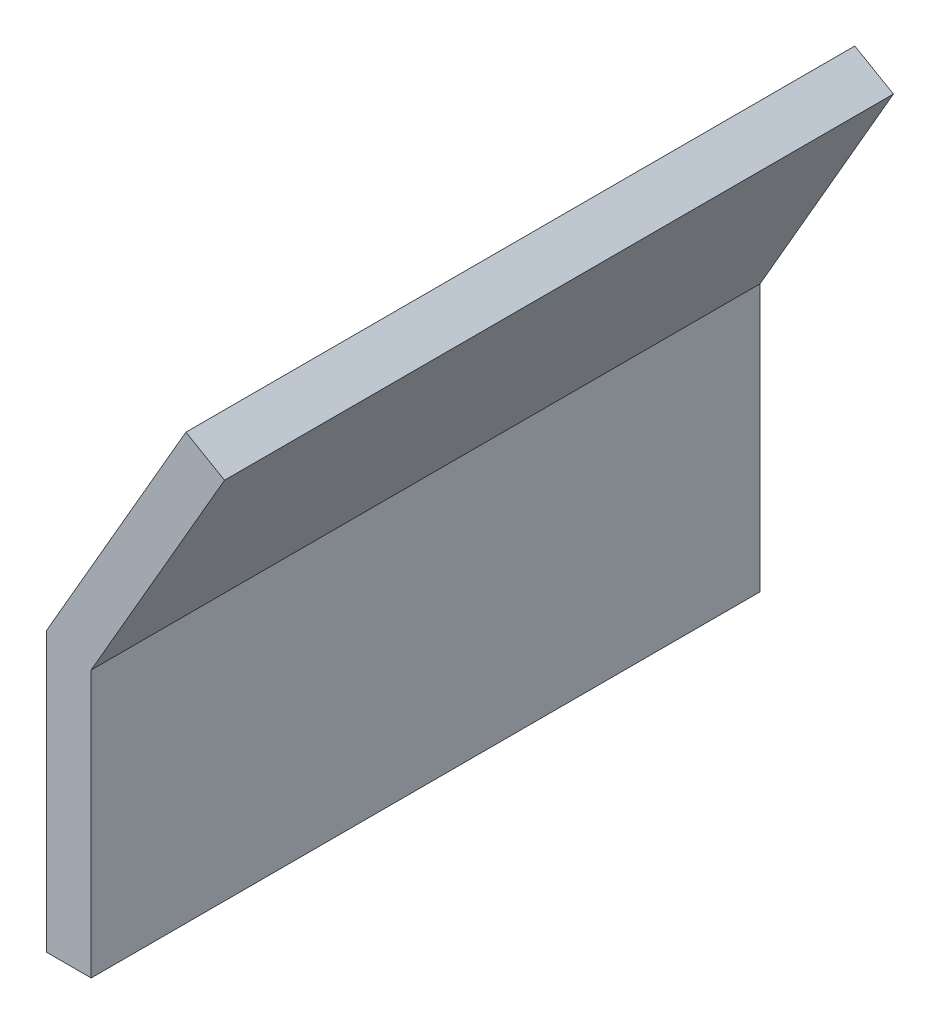
SolidWorks part; units mm, degrees
material "PLA"
ref_plane "Front Plane" through (0, 0, 0) normal (0, 0, 1) x (1, 0, 0)
ref_plane "Top Plane" through (0, 0, 0) normal (0, 1, 0) x (1, 0, 0)
ref_plane "Right Plane" through (0, 0, 0) normal (1, 0, 0) x (0, 0, -1)
sketch "Sketch1" plane through (0, 0, 0) normal (0, 0, 1) x (1, 0, 0)
  line L0 (0, 0) -> (25, 43.3013)
  line L1 (0, 0) -> (0, -50)
  line L2 (8, -2.1436) -> (31.9282, 39.3013)
  line L3 (8, -2.1436) -> (8, -50)
  line L4 (25, 43.3013) -> (31.9282, 39.3013)
  line L5 (0, -50) -> (8, -50)
  dimension "D1" = 50
  dimension "D2" = 50
  dimension "D3" = 150
  dimension "D4" = 8
extrude "Boss-Extrude1" add sketch "Sketch1" along normal mid plane 120
